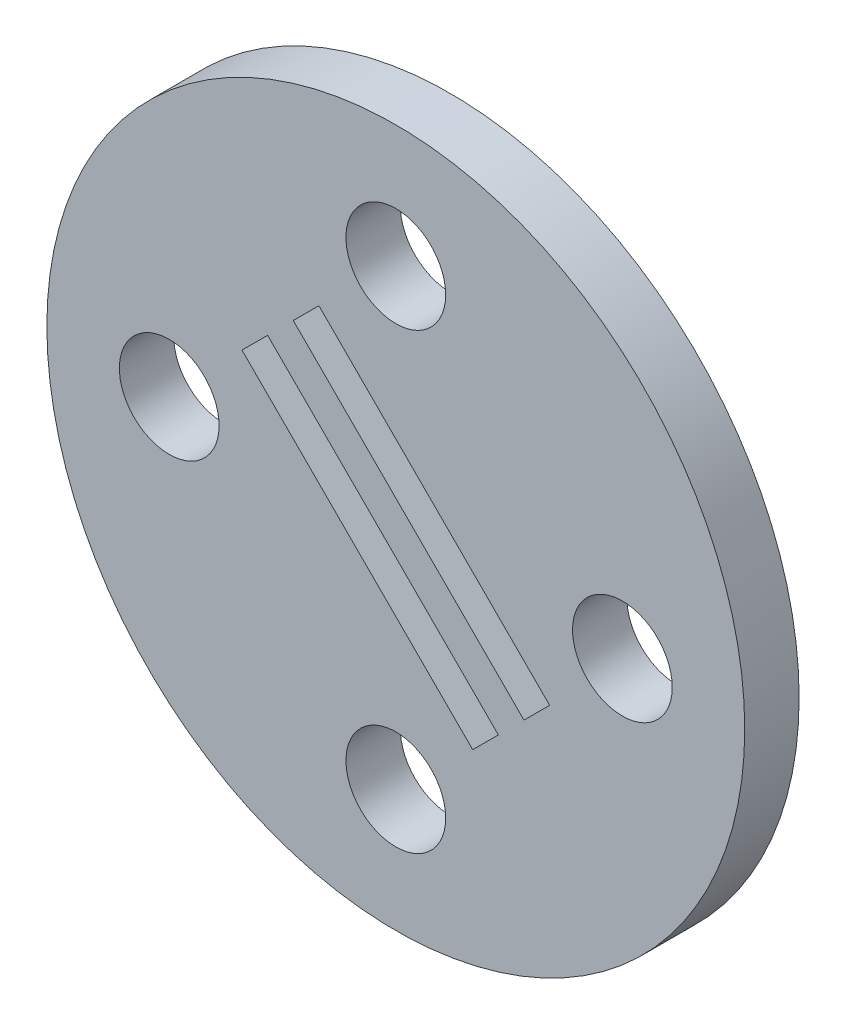
SolidWorks part; units mm, degrees
material "Acrylic (Medium-high impact)"
ref_plane "Front Plane" through (0, 0, 0) normal (0, 0, 1) x (1, 0, 0)
ref_plane "Top Plane" through (0, 0, 0) normal (0, 1, 0) x (1, 0, 0)
ref_plane "Right Plane" through (0, 0, 0) normal (1, 0, 0) x (0, 0, -1)
sketch "Model" plane through (0, 0, 0) normal (0, 0, 1) x (1, 0, 0)
  line L1 (-16.9706, 8.4853) -> (-14.1421, 11.3137)
  line L2 (8.4853, -16.9706) -> (-16.9706, 8.4853)
  line L3 (-11.3137, 14.1421) -> (14.1421, -11.3137)
  line L4 (11.3137, -14.1421) -> (8.4853, -16.9706)
  line L5 (14.1421, -11.3137) -> (16.9706, -8.4853)
  line L6 (16.9706, -8.4853) -> (-8.4853, 16.9706)
  line L7 (-8.4853, 16.9706) -> (-11.3137, 14.1421)
  line L8 (-14.1421, 11.3137) -> (11.3137, -14.1421)
  circle A5 centre (0, 0) radius 38.5
  circle A10 centre (-25, 0) radius 5.5
  circle A11 centre (0, 25) radius 5.5
  circle A12 centre (0, -25) radius 5.5
  circle A13 centre (25, 0) radius 5.5
  dimension "D2" = 11
  dimension "D3" = 4
  dimension "D4" = 77
  dimension "D6" = 25
  dimension "D7" = 25
  dimension "D9" = 36
  dimension "D10" = 25
  dimension "D13" = 25
extrude "Boss-Extrude1" add sketch "Model" along normal blind 6
